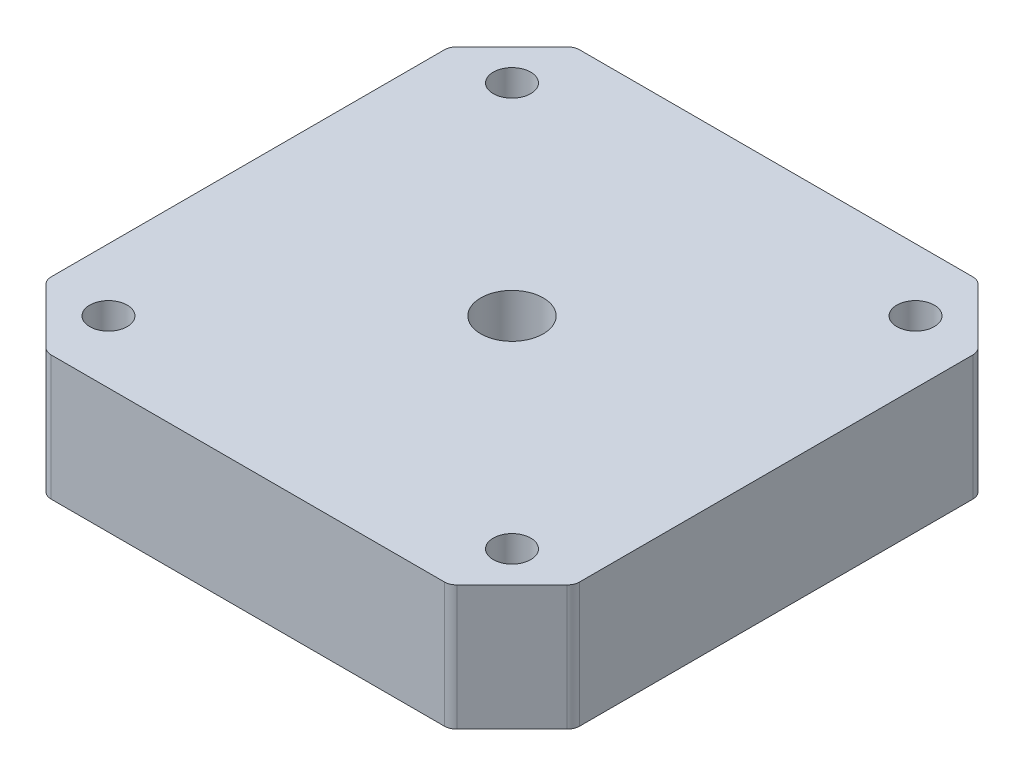
SolidWorks part; units mm, degrees
ref_plane "Front Plane" through (0, 0, 0) normal (0, 0, 1) x (1, 0, 0)
ref_plane "Top Plane" through (0, 0, 0) normal (0, 1, 0) x (1, 0, 0)
ref_plane "Right Plane" through (0, 0, 0) normal (1, 0, 0) x (0, 0, -1)
sketch "Sketch1" plane through (0, 0, 0) normal (0, 1, 0) x (1, 0, 0)
  line L0 (5, 42.3) -> (0, 37.3)
  line L1 (0, 0) -> (42.3, 0)
  line L2 (0, 0) -> (0, 42.3)
  line L3 (0, 42.3) -> (42.3, 42.3)
  line L4 (42.3, 0) -> (42.3, 42.3)
  line L5 (0, 5) -> (5, 0)
  line L6 (37.3, 42.3) -> (42.3, 37.3)
  line L7 (42.3, 5) -> (37.3, 0)
  circle A0 centre (5, 5) radius 1.5
  circle A1 centre (5, 37.3) radius 1.5
  circle A2 centre (37.3, 37.3) radius 1.5
  circle A3 centre (37.3, 5) radius 1.5
  dimension "D5" = 3
  dimension "D7" = 3
  dimension "D9" = 3
  dimension "D10" = 3
  dimension "D1" = 42.3
  dimension "D2" = 42.3
  dimension "D3" = 5
  dimension "D4" = 5
  dimension "D6" = 5
  dimension "D8" = 5
extrude "Boss-Extrude1" add sketch "Sketch1" along normal blind 10 contours L7 L4 L6 L3 L0 L2 L5 L1 A3 A2 A1 A0
fillet "Fillet1" radius 1 1 edges at (0, 5, -5)
fillet "Fillet2" radius 1 1 edges at (5, 5, 0)
fillet "Fillet3" radius 1 1 edges at (37.3, 5, 0)
fillet "Fillet4" radius 1 1 edges at (42.3, 5, -5)
fillet "Fillet5" radius 1 1 edges at (42.3, 5, -37.3)
fillet "Fillet6" radius 1 1 edges at (37.3, 5, -42.3)
fillet "Fillet7" radius 1 1 edges at (5, 5, -42.3)
fillet "Fillet8" radius 1 1 edges at (0, 5, -37.3)
sketch "Sketch2" plane through (0, 10, 0) normal (0, 1, 0) x (1, 0, 0)
  circle A0 centre (21.15, 21.15) radius 2.5
  dimension "D1" = 5
extrude "Cut-Extrude1" cut sketch "Sketch2" against normal blind 10
